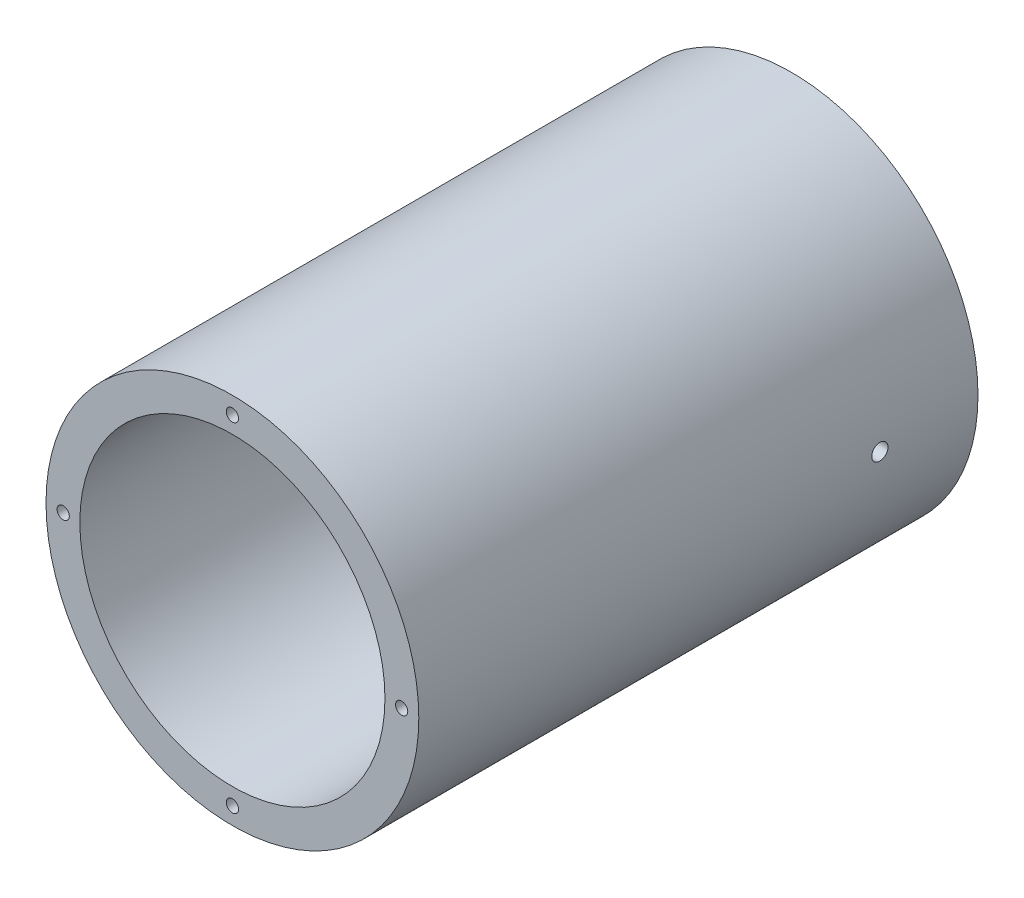
SolidWorks part; units mm, degrees
material "AISI 1020 钢，冷轧"
ref_plane "前视基准面" through (0, 0, 0) normal (0, 0, 1) x (1, 0, 0)
ref_plane "上视基准面" through (0, 0, 0) normal (0, 1, 0) x (1, 0, 0)
ref_plane "右视基准面" through (0, 0, 0) normal (1, 0, 0) x (0, 0, -1)
sketch "草图1" plane through (0, 0, 0) normal (0, 0, 1) x (1, 0, 0)
  circle A0 centre (0, 0) radius 38
  circle A1 centre (0, 0) radius 31.1
  dimension "D1" = 76
  dimension "D2" = 62.2
extrude "凸台-拉伸1" add sketch "草图1" along normal mid plane 114
hole_wizard "M3 螺纹孔1" positions "草图3" profile "草图2" tap size "M3" standard "GB"
sketch "草图3" plane through (0, 0, 57) normal (0, 0, 1) x (1, 0, 0)
  point P0 (0, 34.5)
  point P10 (34.5, 0)
  point P11 (0, -34.5)
  point P12 (-34.5, 0)
  dimension "D1" = 34.5
  dimension "D2" = 4
sketch "草图2" plane through (0, 34.5, 57) normal (1, 0, 0) x (0, -1, 0)
  line L0 (0, 0) -> (0, 9.2511)
  line L1 (0, 9.2511) -> (1.25, 8.5)
  line L2 (1.25, 8.5) -> (1.25, 0)
  line L5 (1.25, 0) -> (0, 0)
  line L10 (0, 9.2511) -> (-1.25, 8.5) construction
  line L11 (0, -6.35) -> (0, 107.95) construction
  dimension "螺纹孔钻头直径" = 2.5
  dimension "螺纹孔钻头深度" = 8.5
  dimension "导头角度" = 118
cosmetic thread "孔螺蚊线3" parameters "D1"=6, "D2"=3
cosmetic thread "孔螺蚊线4" parameters "D1"=6, "D2"=3
cosmetic thread "孔螺蚊线5" parameters "D1"=6, "D2"=3
cosmetic thread "孔螺蚊线6" parameters "D1"=6, "D2"=3
sketch "草图5" plane through (0, 0, -57) normal (0, 0, -1) x (-1, 0, 0)
  circle A0 centre (0, 0) radius 38
  circle A1 centre (0, 0) radius 14
  circle A2 centre (0, 0) radius 38 construction
  dimension "D1" = 28
extrude "凸台-拉伸2" [suppressed] add sketch "草图5" along normal blind 10
hole_wizard "M3 螺纹孔3" positions "草图11" profile "草图13" tap size "M3" standard "GB"
sketch "草图11" plane through (13.8063, 28.9872, -57) normal (0, 0, -1) x (-1, 0, 0)
  line L0 (13.8063, -28.9872) -> (13.8063, -2.0872) construction
  line L3 (13.8063, -28.9872) -> (48.3063, -28.9872) construction
  circle A0 centre (13.8063, -28.9872) radius 34.5
  point P0 (48.3063, -28.9872)
  point P10 (13.8063, -63.4872)
  point P11 (-20.6937, -28.9872)
  point P12 (13.8063, 5.5128)
  dimension "D1" = 69
  dimension "D3" = 90
  dimension "D2" = 4
sketch "草图13" plane through (-34.5, 0, -57) normal (1, 0, 0) x (0, 1, 0)
  line L0 (0, 0) -> (0, 9.2511)
  line L1 (0, 9.2511) -> (1.25, 8.5)
  line L2 (1.25, 8.5) -> (1.25, 0)
  line L5 (1.25, 0) -> (0, 0)
  line L10 (0, 9.2511) -> (-1.25, 8.5) construction
  line L11 (0, -6.35) -> (0, 107.95) construction
  dimension "螺纹孔钻头直径" = 2.5
  dimension "螺纹孔钻头深度" = 8.5
  dimension "导头角度" = 118
cosmetic thread "孔螺蚊线13" parameters "D1"=6, "D2"=3
cosmetic thread "孔螺蚊线15" parameters "D1"=6, "D2"=3
cosmetic thread "孔螺蚊线16" parameters "D1"=6, "D2"=3
cosmetic thread "孔螺蚊线17" parameters "D1"=6, "D2"=3
hole_wizard "M4 螺纹孔1" positions "3D草图1" profile "草图14" tap size "M4" standard "GB" end condition up to next
sketch3d "3D草图1"
  line L0 (-38, 0, -37) -> (38, 0, -37) construction
  line L2 (0, 0, 0) -> (0, 0, -37) construction
  circle A0 centre (0, 0, -57) radius 38 construction
  point P0 (38, 0, -37)
  point P2 (-38, 0, -37)
  point P15 (0, 0, -19)
  dimension "D1" = 20
sketch "草图14" plane through (38, 0, -37) normal (0, 1, 0) x (0, 0, -1)
  line L0 (0, 0) -> (0, 6.9)
  line L1 (0, 6.9) -> (1.65, 6.9)
  line L2 (1.65, 6.9) -> (1.65, 0)
  line L5 (1.65, 0) -> (0, 0)
  line L11 (0, -6.35) -> (0, 107.95) construction
  dimension "通孔螺纹孔钻头直径" = 3.3
  dimension "通孔螺纹孔钻头深度" = 6.9
cosmetic thread "孔螺蚊线18" parameters "D2"=4
cosmetic thread "孔螺蚊线19" parameters "D2"=4
